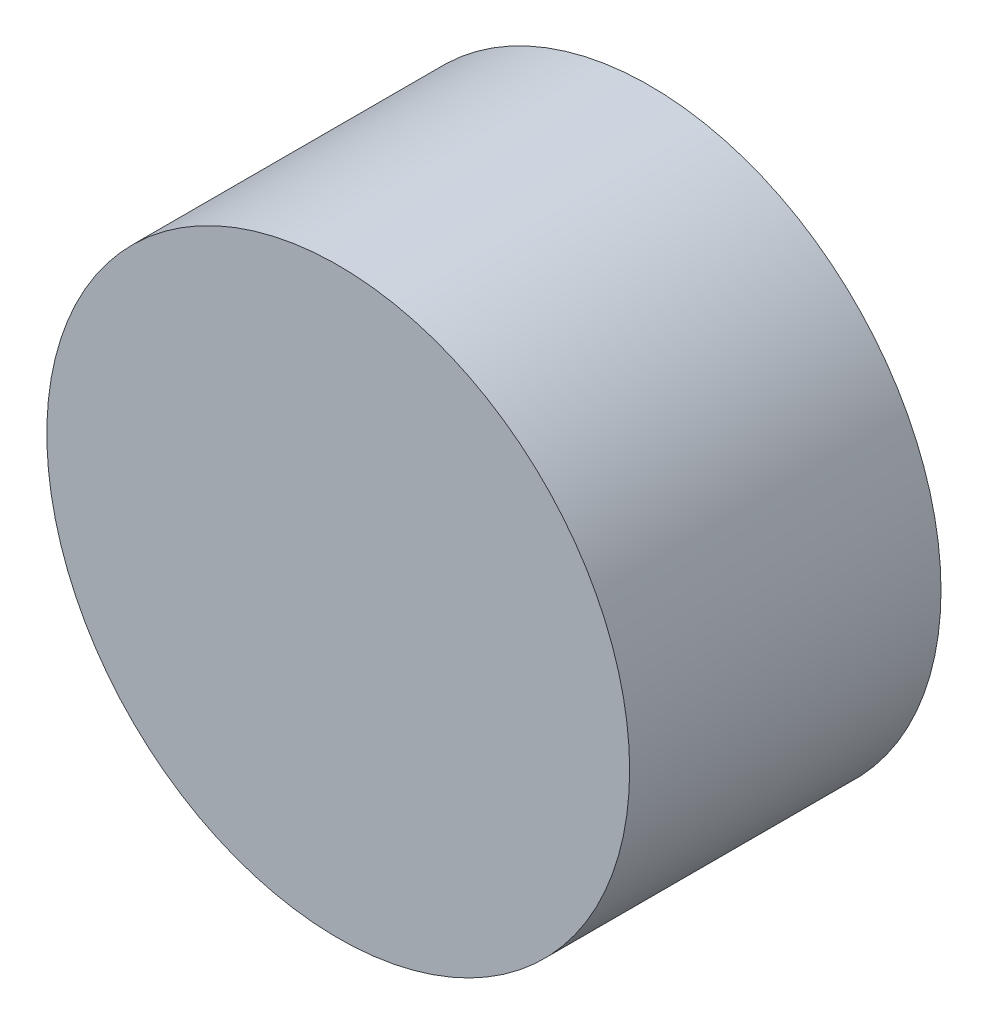
SolidWorks part; units mm, degrees
ref_plane "Front Plane" through (0, 0, 0) normal (0, 0, 1) x (1, 0, 0)
ref_plane "Top Plane" through (0, 0, 0) normal (0, 1, 0) x (1, 0, 0)
ref_plane "Right Plane" through (0, 0, 0) normal (1, 0, 0) x (0, 0, -1)
sketch "Sketch1" plane through (0, 0, 0) normal (0, 0, 1) x (1, 0, 0)
  circle A0 centre (0, 0) radius 15.0762
  dimension "D1" = 30.1523
extrude "Boss-Extrude1" add sketch "Sketch1" along normal blind 16.1087
sketch "Sketch2" plane through (0, 0, 0) normal (0, 0, -1) x (-1, 0, 0)
  circle A0 centre (0, 0) radius 9.3853
  circle A1 centre (0, 0) radius 4.5847
  dimension "D1" = 18.7706
  dimension "D2" = 9.1694
extrude "Cut-Extrude1" cut sketch "Sketch2" against normal blind 4.7498
